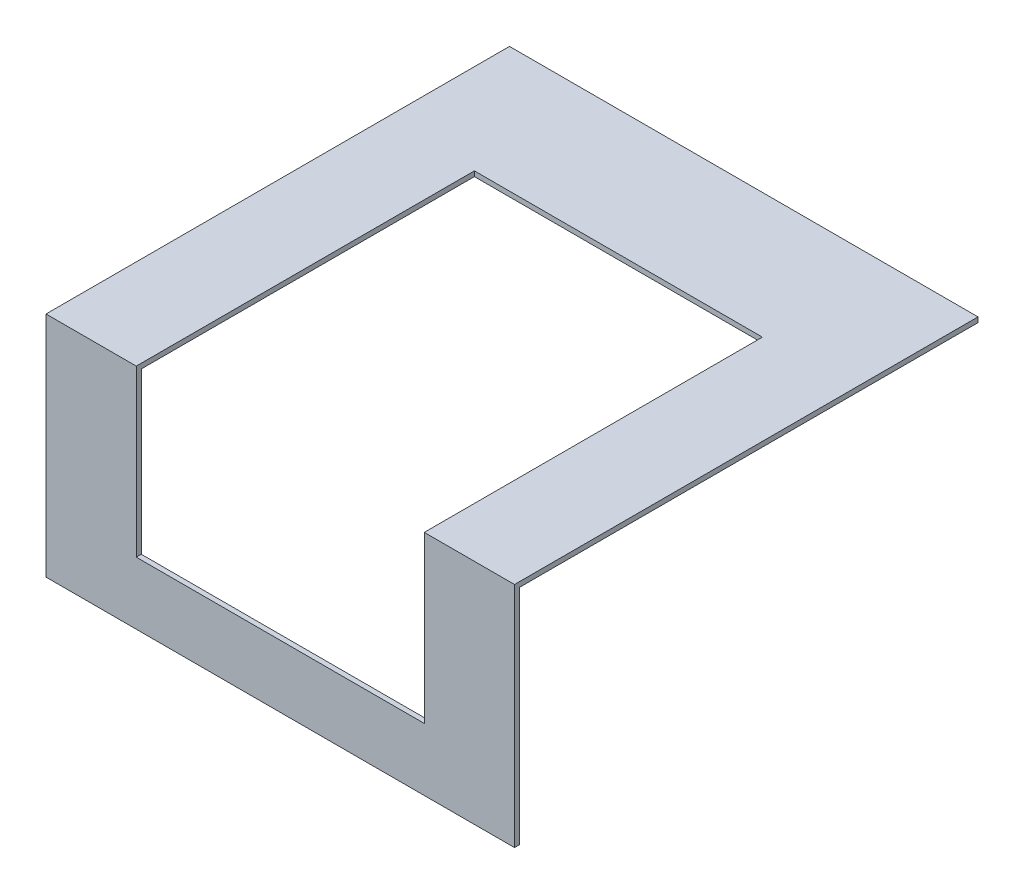
SolidWorks part; units mm, degrees
material "ABS"
ref_plane "Front Plane" through (0, 0, 0) normal (0, 0, 1) x (1, 0, 0)
ref_plane "Top Plane" through (0, 0, 0) normal (0, 1, 0) x (1, 0, 0)
ref_plane "Right Plane" through (0, 0, 0) normal (1, 0, 0) x (0, 0, -1)
sketch "Sketch1" plane through (0, 0, 0) normal (0, 0, 1) x (1, 0, 0)
  line L1 (-233.6, -111.125) -> (233.6, -111.125)
  line L2 (-233.6, -111.125) -> (-233.6, 111.125)
  line L3 (-233.6, 111.125) -> (233.6, 111.125)
  line L4 (233.6, -111.125) -> (233.6, 111.125)
  line L5 (-233.6, -111.125) -> (233.6, 111.125) construction
  line L6 (-233.6, 111.125) -> (233.6, -111.125) construction
  point P0 (0, 0)
  dimension "D1" = 467.2
  dimension "D2" = 222.25
extrude "Boss-Extrude1" add sketch "Sketch1" along normal blind 5
sketch "Sketch2" plane through (0, 111.125, 0) normal (0, 1, 0) x (1, 0, 0)
  line L0 (-233.6, -5) -> (233.6, -5)
  line L1 (-233.6, -5) -> (-233.6, 457.2)
  line L2 (233.6, -5) -> (233.6, 457.2)
  line L3 (-233.6, 457.2) -> (233.6, 457.2)
  dimension "D1" = 462.2
extrude "Boss-Extrude2" add sketch "Sketch2" along normal blind 5
sketch "Sketch3" plane through (0, 116.125, 0) normal (0, 1, 0) x (1, 0, 0)
  line L0 (-233.6, -5) -> (233.6, -5) construction
  line L1 (-143.6, -342.2) -> (143.6, -342.2)
  line L2 (-143.6, -342.2) -> (-143.6, 332.2)
  line L3 (-143.6, 332.2) -> (143.6, 332.2)
  line L4 (143.6, -342.2) -> (143.6, 332.2)
  line L5 (-143.6, -342.2) -> (143.6, 332.2) construction
  line L6 (-143.6, 332.2) -> (143.6, -342.2) construction
  line L7 (-233.6, 457.2) -> (-233.6, -5) construction
  line L8 (233.6, 457.2) -> (-233.6, 457.2) construction
  point P0 (0, -5)
  dimension "D1" = 90
  dimension "D2" = 125
extrude "Cut-Extrude1" cut sketch "Sketch3" against normal blind 165
